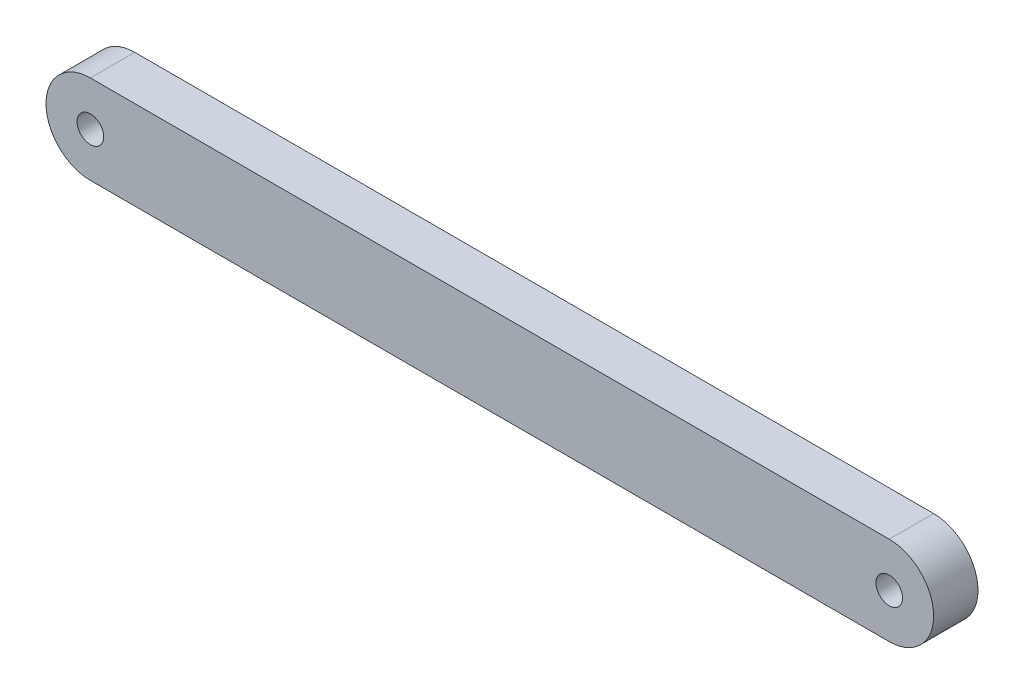
SolidWorks part; units mm, degrees
ref_plane "Plan de face" through (0, 0, 0) normal (0, 0, 1) x (1, 0, 0)
ref_plane "Plan de dessus" through (0, 0, 0) normal (0, 1, 0) x (1, 0, 0)
ref_plane "Plan de droite" through (0, 0, 0) normal (1, 0, 0) x (0, 0, -1)
sketch "Esquisse1" plane through (0, 0, 0) normal (0, 0, 1) x (1, 0, 0)
  line L0 (-45, 0) -> (45, 0) construction
  line L1 (-45, 5) -> (45, 5)
  line L2 (-45, -5) -> (45, -5)
  arc A0 (-45, 5) -> (-45, -5) centre (-45, 0) ccw
  arc A1 (45, -5) -> (45, 5) centre (45, 0) ccw
  circle A2 centre (-45, 0) radius 1.5
  circle A3 centre (45, 0) radius 1.5
  point P2 (0, 0)
  dimension "D1" = 5
  dimension "D3" = 3
  dimension "D4" = 3
  dimension "D2" = 90
extrude "Boss.-Extru.1" add sketch "Esquisse1" along normal blind 5
